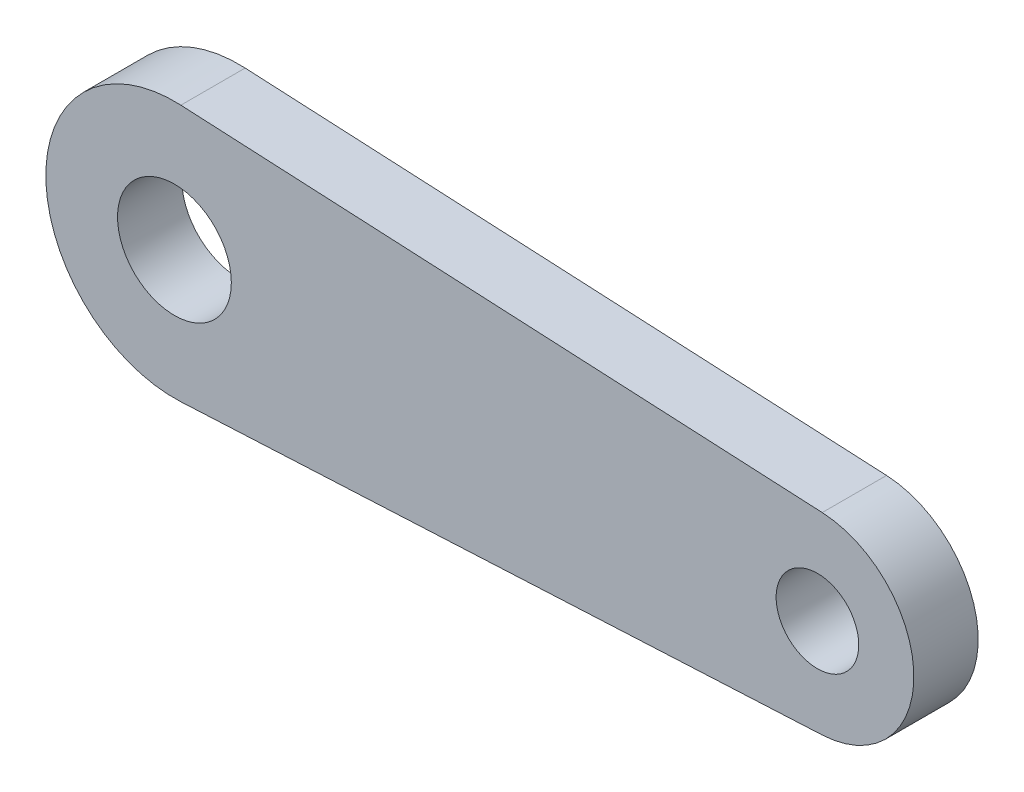
SolidWorks part; units mm, degrees
ref_plane "Front Plane" through (0, 0, 0) normal (0, 0, 1) x (1, 0, 0)
ref_plane "Top Plane" through (0, 0, 0) normal (0, 1, 0) x (1, 0, 0)
ref_plane "Right Plane" through (0, 0, 0) normal (1, 0, 0) x (0, 0, -1)
sketch "Sketch1" plane through (0, 0, 0) normal (0, 0, 1) x (1, 0, 0)
  line L0 (0, 0) -> (25.4, 0) construction
  line L1 (0.254, -5.0736) -> (25.5905, -3.8052)
  line L3 (0.254, 5.0736) -> (25.5905, 3.8052)
  arc A4 (0.254, 5.0736) -> (0.254, -5.0736) centre (0, 0) ccw
  arc A5 (25.5905, 3.8052) -> (25.5905, -3.8052) centre (25.4, 0) cw
  point P0 (0, 0)
  point P1 (1.682, 0)
  point P7 (0, 0)
  dimension "D3" = 3.81
  dimension "D2" = 5.08
  dimension "D1" = 25.4
extrude "Boss-Extrude1" add sketch "Sketch1" along normal blind 2.54
sketch "Sketch6" plane through (0, 0, 2.54) normal (0, 0, 1) x (1, 0, 0)
  line L0 (0, 0) -> (25.4, 0) construction
  line L1 (0, 0) -> (25.4, 0)
hole_wizard "#8 Clearance Hole1" positions "3DSketch5" profile "Sketch7" hole size "#8" standard "ANSI Inch" end condition up to next
sketch3d "3DSketch5"
  point P0 (0, 0, 2.54)
sketch "Sketch7" plane through (0, 0, 2.54) normal (1, 0, 0) x (0, -1, 0)
  line L0 (0, 0) -> (0, 2.54)
  line L1 (0, 2.54) -> (2.2479, 2.54)
  line L2 (2.2479, 2.54) -> (2.2479, 0)
  line L5 (2.2479, 0) -> (0, 0)
  line L11 (0, -6.35) -> (0, 107.95) construction
  dimension "Thru Hole Dia." = 4.4958
  dimension "Thru Hole Depth" = 2.54
hole_wizard "#4 Clearance Hole1" positions "3DSketch6" profile "Sketch8" hole size "#4" standard "ANSI Inch" end condition up to next
sketch3d "3DSketch6"
  point P0 (25.4, 0, 2.54)
sketch "Sketch8" plane through (25.4, 0, 2.54) normal (1, 0, 0) x (0, -1, 0)
  line L0 (0, 0) -> (0, 2.54)
  line L1 (0, 2.54) -> (1.6319, 2.54)
  line L2 (1.6319, 2.54) -> (1.6319, 0)
  line L5 (1.6319, 0) -> (0, 0)
  line L11 (0, -6.35) -> (0, 107.95) construction
  dimension "Thru Hole Dia." = 3.2639
  dimension "Thru Hole Depth" = 2.54
